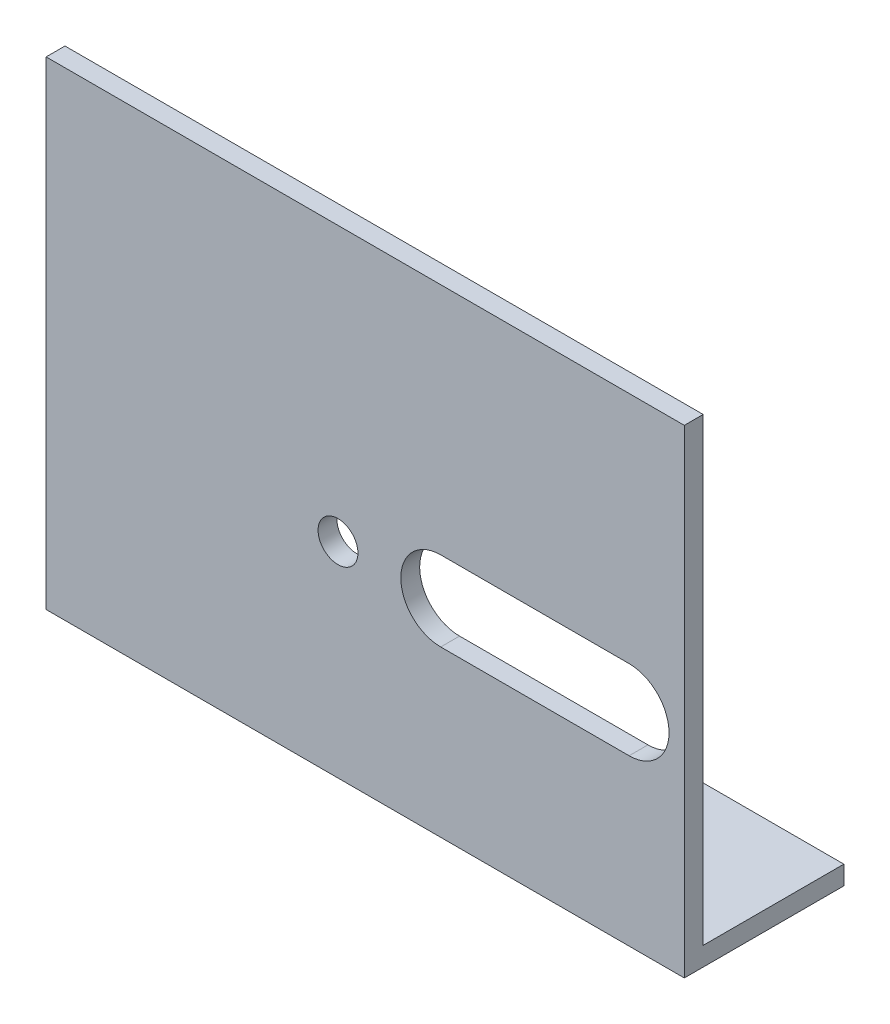
SolidWorks part; units mm, degrees
ref_plane "Alzado" through (0, 0, 0) normal (0, 0, 1) x (1, 0, 0)
ref_plane "Planta" through (0, 0, 0) normal (0, 1, 0) x (1, 0, 0)
ref_plane "Vista lateral" through (0, 0, 0) normal (1, 0, 0) x (0, 0, -1)
sketch "Croquis1" plane through (0, 0, 0) normal (1, 0, 0) x (0, 0, -1)
  line L0 (0, 76.2) -> (0, 0)
  line L1 (0, 0) -> (25.4, 0)
  line L2 (25.4, 0) -> (25.4, 3)
  line L3 (25.4, 3) -> (3, 3)
  line L4 (3, 3) -> (3, 76.2)
  line L5 (3, 76.2) -> (0, 76.2)
  dimension "D1" = 76.2
  dimension "D2" = 25.4
  dimension "D3" = 3
  dimension "D4" = 3
extrude "Saliente-Extruir1" add sketch "Croquis1" along normal mid plane 101.6
sketch "Croquis2" plane through (0, 0, 0) normal (0, 0, 1) x (1, 0, 0)
  line L0 (42.0158, 32.6) -> (12.0158, 32.6) construction
  line L1 (42.0158, 26.25) -> (12.0158, 26.25)
  line L2 (42.0158, 38.95) -> (12.0158, 38.95)
  line L3 (50.8, 0) -> (-50.8, 0) construction
  line L4 (5.6658, 32.6) -> (-4.3342, 32.6) construction
  arc A0 (42.0158, 26.25) -> (42.0158, 38.95) centre (42.0158, 32.6) ccw
  arc A1 (12.0158, 38.95) -> (12.0158, 26.25) centre (12.0158, 32.6) ccw
  circle A2 centre (-4.3342, 32.6) radius 3.175
  point P2 (27.0158, 32.6)
  dimension "D2" = 6.35
  dimension "D5" = 6.35
  dimension "D1" = 32.6
  dimension "D3" = 30
  dimension "D4" = 10
extrude "Cortar-Extruir1" cut sketch "Croquis2" against normal through all
